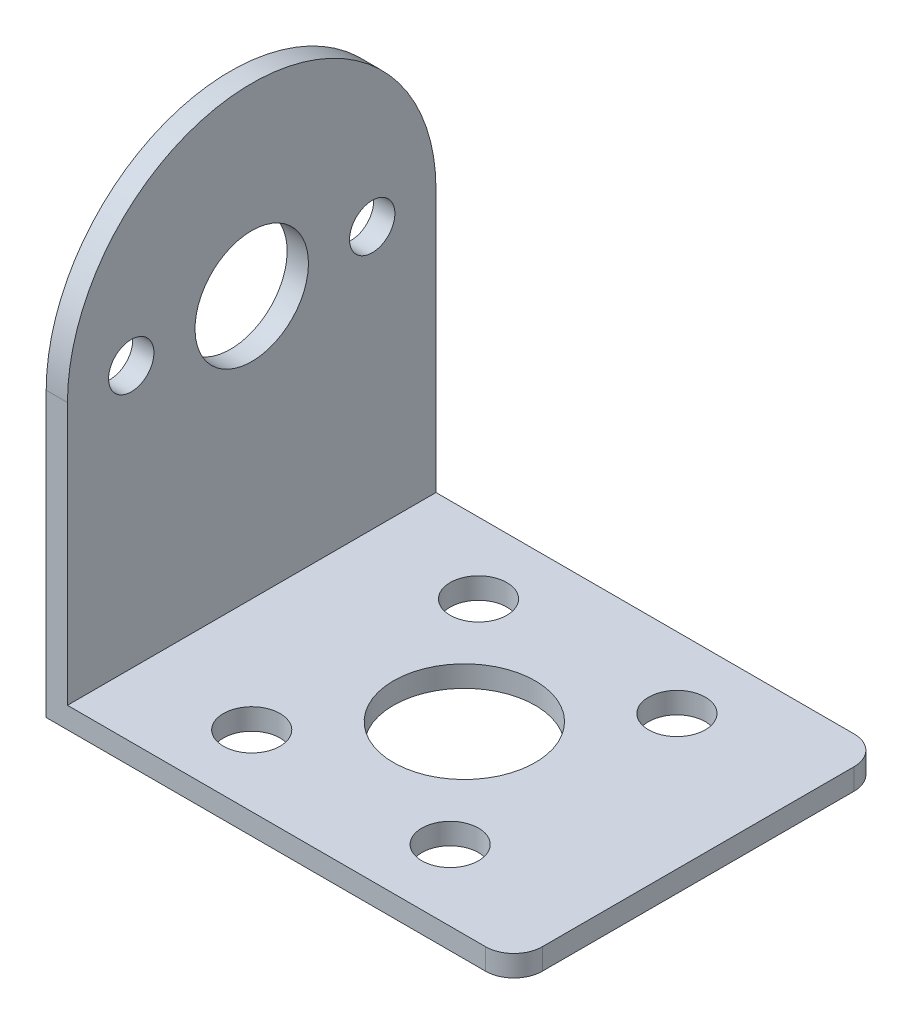
SolidWorks part; units mm, degrees
ref_plane "Front Plane" through (0, 0, 0) normal (0, 0, 1) x (1, 0, 0)
ref_plane "Top Plane" through (0, 0, 0) normal (0, 1, 0) x (1, 0, 0)
ref_plane "Right Plane" through (0, 0, 0) normal (1, 0, 0) x (0, 0, -1)
sketch "Sketch2" plane through (0, 0, 0) normal (0, 0, 1) x (1, 0, 0)
  line L1 (0, 0) -> (33, 0)
  line L2 (0, 0) -> (0, 33)
  line L3 (0, 33) -> (1.5, 33)
  line L4 (33, 0) -> (33, 1.5)
  line L7 (33, 1.5) -> (1.5, 1.5)
  line L8 (1.5, 33) -> (1.5, 1.5)
  dimension "D1" = 33
  dimension "D2" = 33
  dimension "D3" = 1.5
  dimension "D4" = 1.5
extrude "Boss-Extrude1" add sketch "Sketch2" along normal blind 26
fillet "Fillet1" radius 2 2 edges at (33, 0.75, 0) (33, 0.75, 26)
sketch "Sketch3" plane through (0, 1.5, 0) normal (0, 1, 0) x (1, 0, 0)
  line L0 (31, -26) -> (1.5, -26) construction
  line L1 (33, -24) -> (33, -2) construction
  circle A0 centre (16.5, -13) radius 5
  circle A1 centre (9.5, -5) radius 2
  circle A2 centre (23.5, -5) radius 2
  circle A3 centre (23.5, -21) radius 2
  circle A4 centre (9.5, -21) radius 2
  dimension "D1" = 10
  dimension "D2" = 4
  dimension "D3" = 4
  dimension "D4" = 4
  dimension "D5" = 4
  dimension "D6" = 14
  dimension "D7" = 16
  dimension "D8" = 14
  dimension "D9" = 16
  dimension "D10" = 14
  dimension "D11" = 7
  dimension "D12" = 8
  dimension "D13" = 16
  dimension "D14" = 5
  dimension "D15" = 16.5
extrude "Cut-Extrude1" cut sketch "Sketch3" against normal through all
sketch "Sketch4" plane through (1.5, 0, 0) normal (1, 0, 0) x (0, 0, -1)
  line L0 (-26, 1.5) -> (-26, 33) construction
  line L1 (-26, 33) -> (0, 33) construction
  line L4 (-26, 20) -> (-26, 38.5971)
  line L5 (-26, 38.5971) -> (0, 38.5971)
  line L6 (0, 20) -> (0, 38.5971)
  arc A0 (0, 20) -> (-26, 20) centre (-13, 20) ccw
  circle A1 centre (-13, 20) radius 4
  circle A2 centre (-21.5, 20) radius 1.6
  circle A3 centre (-4.5, 20) radius 1.6
  dimension "D1" = 26
  dimension "D4" = 8
  dimension "D5" = 3.2
  dimension "D6" = 3.2
  dimension "D2" = 13
  dimension "D3" = 13
  dimension "D7" = 17
  dimension "D8" = 8.5
  dimension "D9" = 13
  dimension "D10" = 13
extrude "Cut-Extrude2" cut sketch "Sketch4" against normal through all
